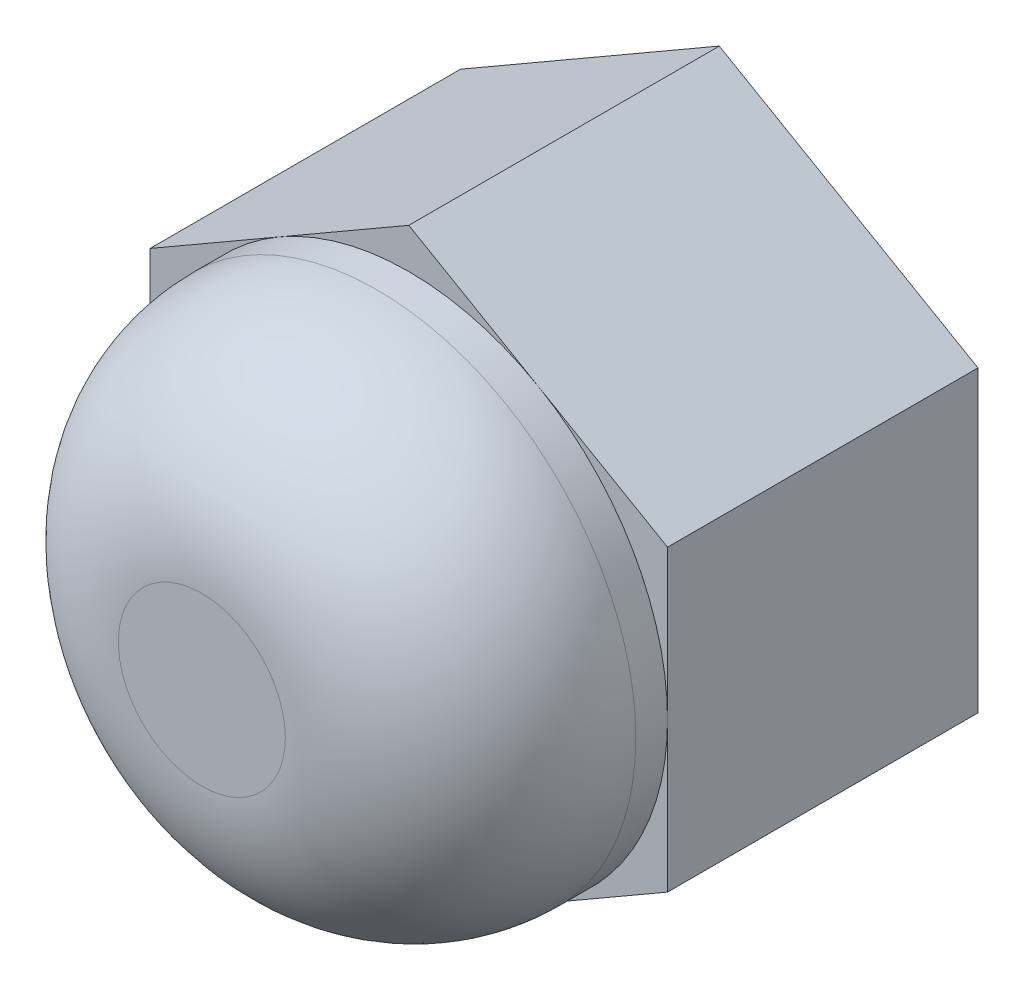
SolidWorks part; units mm, degrees
ref_plane "Front Plane" through (0, 0, 0) normal (1, 0, 0) x (0, 1, 0)
ref_plane "Top Plane" through (0, 0, 0) normal (0, 0, 1) x (0, 1, 0)
ref_plane "Right Plane" through (0, 0, 0) normal (0, 1, 0) x (-1, 0, 0)
sketch "Sketch1" plane through (0, 0, 0) normal (0, 0, 1) x (0, 1, 0)
  line L1 (8.6603, 0) -> (4.3301, 7.5)
  line L2 (4.3301, 7.5) -> (-4.3301, 7.5)
  line L3 (-4.3301, 7.5) -> (-8.6603, 0)
  line L4 (-8.6603, 0) -> (-4.3301, -7.5)
  line L5 (-4.3301, -7.5) -> (4.3301, -7.5)
  line L6 (4.3301, -7.5) -> (8.6603, 0)
  circle A0 centre (0, 0) radius 7.5
  circle A1 centre (0, 0) radius 3.9
  circle A2 centre (0, 0) radius 7.5 construction
  dimension "D1" = 15
  dimension "7.8mm" = 7.8
  dimension "D3" = 15
extrude "Boss-Extrude1" add sketch "Sketch1" along normal blind 9 contours A0 L2 L3 | A0 A1 | A0 L1 L2 | A0 L3 L4 | A0 L6 L1 | A0 L5 L6 | A0 L4 L5
sketch "Sketch2" plane through (0, 0, 9) normal (0, 0, 1) x (1, 0, 0)
  line L0 (7.5, 4.3301) -> (0, 8.6603) construction
  circle A0 centre (0, 0) radius 7.5
extrude "Boss-Extrude2" add sketch "Sketch2" along normal blind 6
fillet "Fillet1" radius 5.08 1 edges at (7.5, 0, 15)
fillet "Fillet2" radius 0.254 1 edges at (3.9, 0, 0)
